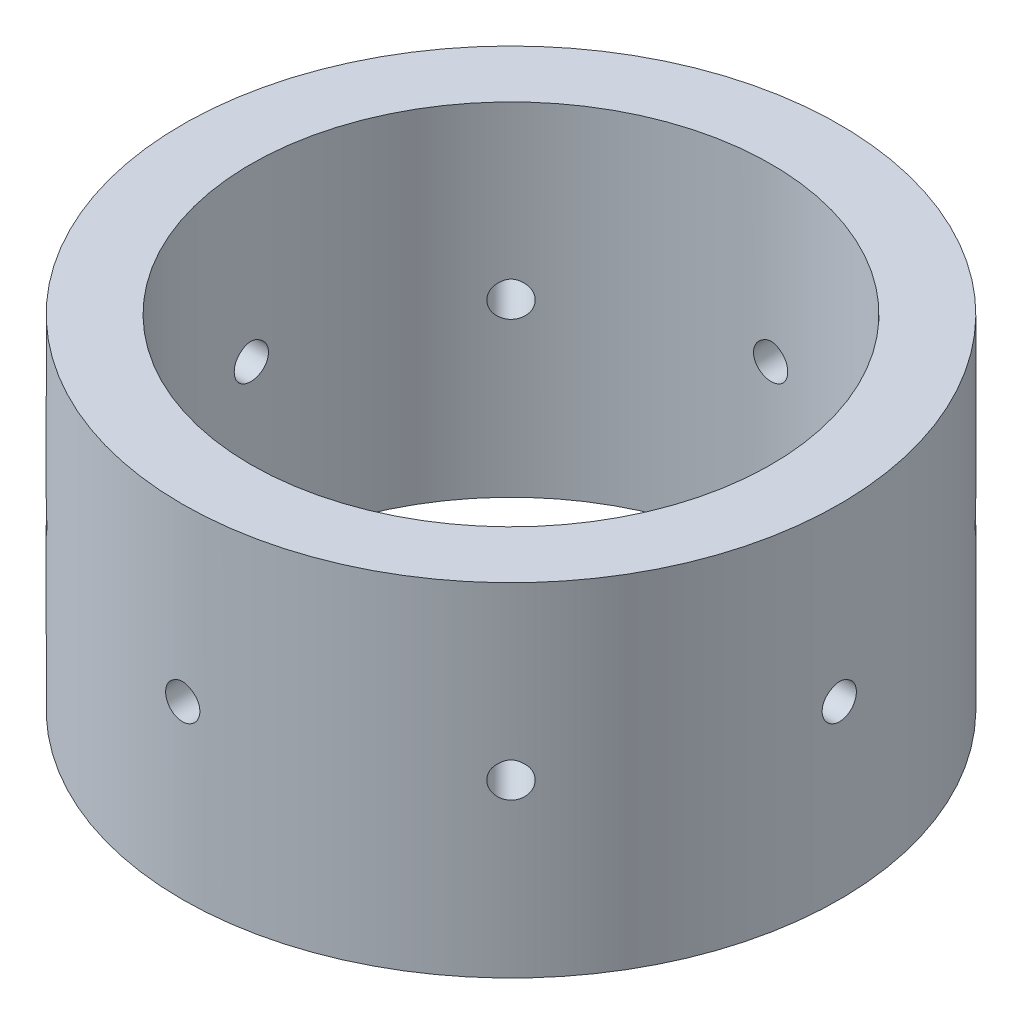
SolidWorks part; units mm, degrees
ref_plane "Front Plane" through (0, 0, 0) normal (0, 0, 1) x (1, 0, 0)
ref_plane "Top Plane" through (0, 0, 0) normal (0, 1, 0) x (1, 0, 0)
ref_plane "Right Plane" through (0, 0, 0) normal (1, 0, 0) x (0, 0, -1)
sketch "Sketch3" plane through (0, 0, 0) normal (0, 1, 0) x (1, 0, 0)
  circle A0 centre (0, 0) radius 48
  circle A1 centre (0, 0) radius 38
  dimension "D2" = 76
  dimension "D1" = 10
extrude "Boss-Extrude1" add sketch "Sketch3" along normal blind 50
ref_plane "Plane2" through (48, 0, 0) normal (1, 0, 0) x (0, 0, -1)
sketch "Sketch5" plane through (48, 0, 0) normal (1, 0, 0) x (0, 0, -1)
  line L0 (0, 0) -> (0, 50) construction
  line L1 (38, 50) -> (-38, 50) construction
  line L2 (-55.8566, 10) -> (-56.1948, 10) construction
  line L3 (-56.1948, 10) -> (55.6312, 10) construction
  line L4 (0, 25) -> (1.25, 27.1651) construction
  line L5 (0, 25) -> (-1.25, 27.1651) construction
  arc A0 (-1.25, 27.1651) -> (1.25, 27.1651) centre (0, 25) ccw
  spline S0 degree 2 poles (1.25, 27.1651) (0, 28.0044) (-1.25, 27.1651) knots 0 0 0 1 1 1
  point P9 (0, 27.5453)
  point P10 (0, 27.6189)
  point P14 (0, 27.5847)
  dimension "D1" = 5
  dimension "D3" = 30
  dimension "D2" = 30
extrude "Cut-Extrude1" cut sketch "Sketch5" against normal up to next
pattern_circular "CirPattern1" count 8 over 360 about axis through (0, 50, 0) along (0, -1, 0) of "Cut-Extrude1"
equation "\"circulo grande\"= 100"
equation "\"circulo pequeño\"= 76"
equation "\"D2@Sketch3\"=\"circulo pequeño\""
equation "\"ancho\"= 50"
equation "\"Boss-Extrude1@Boss-Extrude1\"=\"ancho\""
equation "\"circulo tornillo\"= 5mm"
equation "\"D1@Sketch5\"=\"circulo tornillo\""
